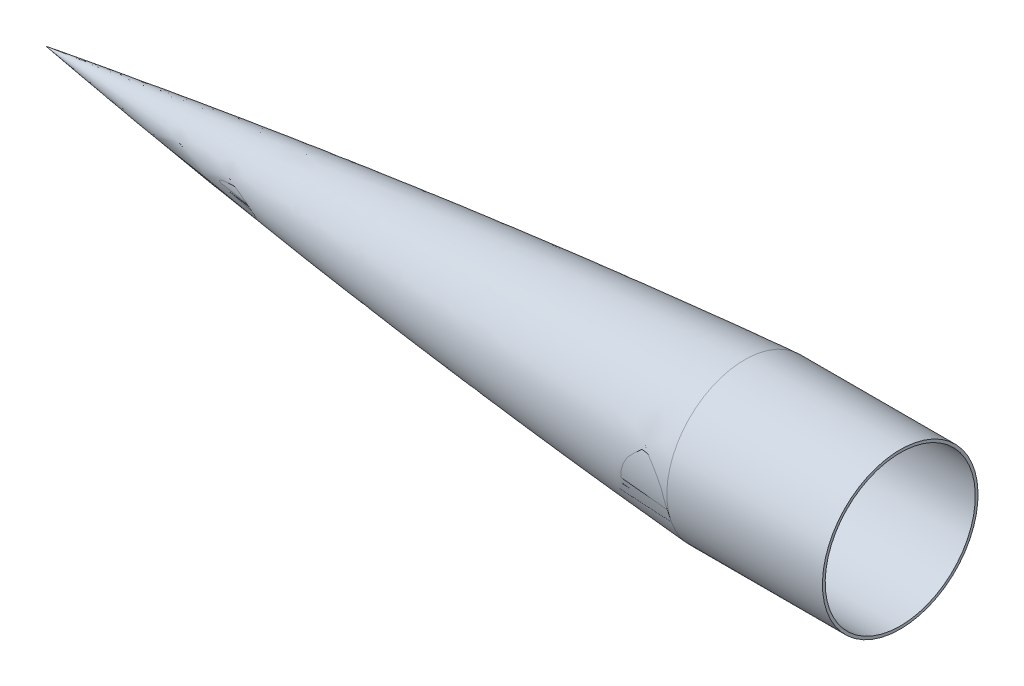
SolidWorks part; units mm, degrees
material "C-Glass Fiber"
ref_plane "Płaszczyzna przednia" through (0, 0, 0) normal (0, 0, 1) x (1, 0, 0)
ref_plane "Płaszczyzna górna" through (0, 0, 0) normal (0, 1, 0) x (1, 0, 0)
ref_plane "Płaszczyzna prawa" through (0, 0, 0) normal (1, 0, 0) x (0, 0, -1)
ref_plane "Plane1" through (0, 0, 0) normal (0, 0, -1) x (-1, 0, 0)
sketch "Sketch1" plane through (0, 0, 0) normal (0, 0, -1) x (-1, 0, 0)
  line L2 (-763.2353, 0) -> (0, 0) construction
  line L6 (-10.2953, 0) -> (0, 0)
  line L7 (-763.3824, 83.0054) -> (-763.3824, 85)
  line L8 (-763.3824, 85) -> (-763.2353, 85)
  arc A0 (0, 0) -> (-763.2353, 85) centre (-1520.6726, -10185.346) ccw
  arc A2 (-10.2953, 0) -> (-763.3824, 83.0054) centre (-1514.0975, -10185.8288) ccw
  dimension "D1" = 85
revolve "Revolve1" add sketch "Sketch1" angle 360 about L2
sketch "Sketch3" plane through (0, 0, 0) normal (0, 0, -1) x (-1, 0, 0)
  line L0 (-763.2353, 85) -> (-763.2353, 76.3847)
  line L1 (-763.2353, 0) -> (0, 0) construction
  line L2 (-755.2353, 76.3847) -> (-763.2353, 76.3847)
  line L3 (-50, 7.258) -> (-50, 2)
  arc A0 (-50, 7.258) -> (-763.2353, 85) centre (-1521.8298, -10185.2606) ccw
  arc A1 (-50, 2) -> (-755.2353, 76.3847) centre (-1481.3517, -10188.2033) ccw
revolve "Revolve2" add sketch "Sketch3" angle 5 about L1
pattern_circular "CirPattern2" count 10 over 360 about axis through (0, 0, 0) along (1, 0, 0) of "Revolve2"
sketch "Sketch10" plane through (0, 0, 0) normal (0, 0, -1) x (-1, 0, 0)
  line L0 (-50, 7.258) -> (-50, 0)
  line L1 (-763.2353, 0) -> (0, 0) construction
  line L2 (-50, 0) -> (-48.2757, 0)
  line L3 (-48.2757, 0) -> (-48.327, 6.9186)
  line L4 (-48.327, 6.9186) -> (-50, 7.258)
revolve "Revolve3" add sketch "Sketch10" angle 360 about L1
sketch "Sketch14" plane through (0, 0, 0) normal (0, 0, -1) x (-1, 0, 0)
  line L0 (-763.2353, 85) -> (-763.2353, -85) construction
  line L1 (-763.2353, 0) -> (-933.2353, 0) construction
  line L2 (-933.2353, 0) -> (-933.2353, 85) construction
  line L3 (-933.2353, 85) -> (-763.2353, 85)
  line L5 (-933.2353, 82) -> (-933.2353, 85)
  line L7 (-933.2353, 82) -> (-763.2353, 82)
  line L8 (-763.2353, 82) -> (-763.2353, 85)
  arc A0 (-763.2353, -85) -> (0, 0) centre (-1520.6726, 10185.346) ccw construction
revolve "Revolve4" add sketch "Sketch14" angle 360 about L1
